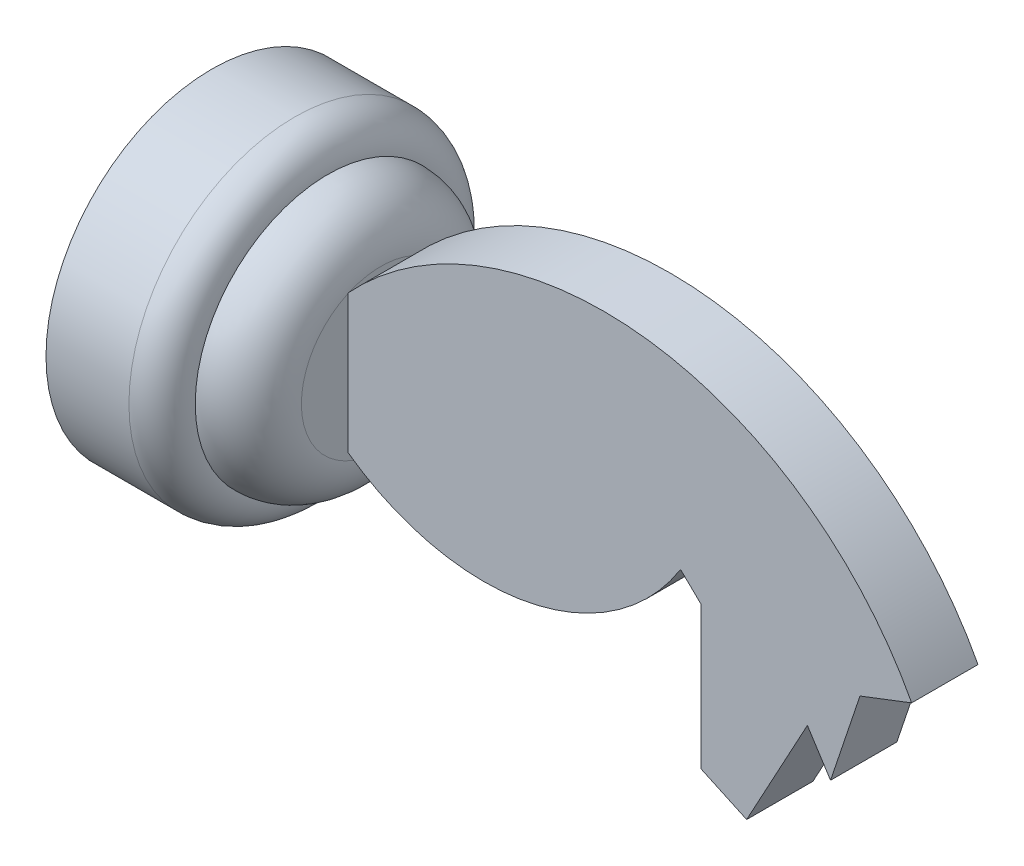
SolidWorks part; units mm, degrees
ref_plane "Спереди" through (0, 0, 0) normal (0, 0, 1) x (1, 0, 0)
ref_plane "Сверху" through (0, 0, 0) normal (0, 1, 0) x (1, 0, 0)
ref_plane "Справа" through (0, 0, 0) normal (1, 0, 0) x (0, 0, -1)
other "Configuration Table"
sketch "Эскиз1" plane through (0, 0, 0) normal (0, 0, 1) x (1, 0, 0)
  line L0 (0, 0) -> (71.2267, 0) construction
sketch "попа" plane through (0, 0, 0) normal (0, 0, 1) x (1, 0, 0)
  line L1 (1, 10) -> (6, 10)
  line L3 (0, 0) -> (71.2267, 0) construction
  line L7 (11.2, 4.8) -> (11.2, 0)
  line L8 (11.2, 0) -> (0, 0)
  line L9 (8, 0) -> (8, 8)
  line L10 (11.2, 2.4) -> (11.2, 0)
  line L11 (0, 0) -> (-9.6864, 0) construction
  line L12 (6, 10) -> (6, 0)
  line L16 (2, 0) -> (4.5, 0)
  line L17 (2, 0) -> (2, 5.25)
  line L18 (2, 5.25) -> (4.5, 5.25)
  line L19 (4.5, 5.25) -> (4.5, 0)
  line L20 (8, 8) -> (6, 8) construction
  line L21 (1, 10) -> (1, 0)
  line L22 (6, 0) -> (8, 0)
  arc A0 (6, 10) -> (8, 8) centre (6, 8) cw
  arc A1 (11.2, 4.8) -> (8, 8) centre (8, 4.8) ccw
  dimension "D6" = 10
  dimension "D7" = 3.2
  dimension "D9" = 5.25
  dimension "D10" = 2.5
  dimension "D8" = 1
  dimension "D1" = 8
  dimension "D2" = 5
  dimension "D3" = 11.2
  dimension "D4" = 4.8
  dimension "D5" = 8
revolve "Повернуть1" add sketch "попа" angle 360 about L0
sketch "вверх" plane through (0, 0, 0) normal (0, 0, 1) x (1, 0, 0)
  line L0 (11.2, 0) -> (11.2, 4.4)
  line L1 (11.2, -4.8) -> (11.2, 4.8) construction
  line L2 (11.2, 0) -> (45.2, 0)
  line L3 (0, 0) -> (71.2267, 0) construction
  line L5 (11.2, 0) -> (11.2, -3.915)
  line L6 (42.083, -1.2) -> (42.083, 0)
  line L7 (40.3075, -6.49) -> (40.3075, 0)
  line L8 (38.912, -4.32) -> (38.912, 0)
  line L9 (31.2635, 0) -> (32.499, -1.1973)
  line L10 (32.499, -1.1973) -> (32.499, -9.7973)
  line L11 (32.499, -9.7973) -> (35.2487, -11.07)
  line L12 (35.2487, -11.07) -> (38.912, -4.32)
  line L13 (38.912, -4.32) -> (40.3075, -6.49)
  line L14 (40.3075, -6.49) -> (42.083, -1.2)
  line L15 (42.083, -1.2) -> (45.2, 0)
  line L16 (35.2487, -11.07) -> (35.2487, 0)
  arc A1 (31.2635, 0) -> (11.2, -3.915) centre (19.3994, 7.4327) cw
  arc A2 (11.2, 4.4) -> (45.2, 0) centre (26.6431, -9.8306) cw
  dimension "D3" = 21
  dimension "D6" = 14
  dimension "D7" = 8.6
  dimension "D1" = 4.4
  dimension "D2" = 34
  dimension "D4" = 20.0635
  dimension "D5" = 3.915
  dimension "D8" = 1.7204
  dimension "D9" = 3.03
  dimension "D10" = 7.68
  dimension "D11" = 2.58
  dimension "D12" = 5.58
  dimension "D13" = 3.34
  dimension "D14" = 13.9365
  dimension "D15" = 1.2
  dimension "D16" = 6.49
  dimension "D17" = 4.32
  dimension "D18" = 11.07
extrude "верх" add sketch "вверх" along normal mid plane 4 contours A2 L0 L2 | A1 L2 L5 | L16 L12 L8 L2 | L11 L16 L2 L9 L10 | L7 L14 L6 L2 | L8 L13 L7 L2 | L6 L15 L2
